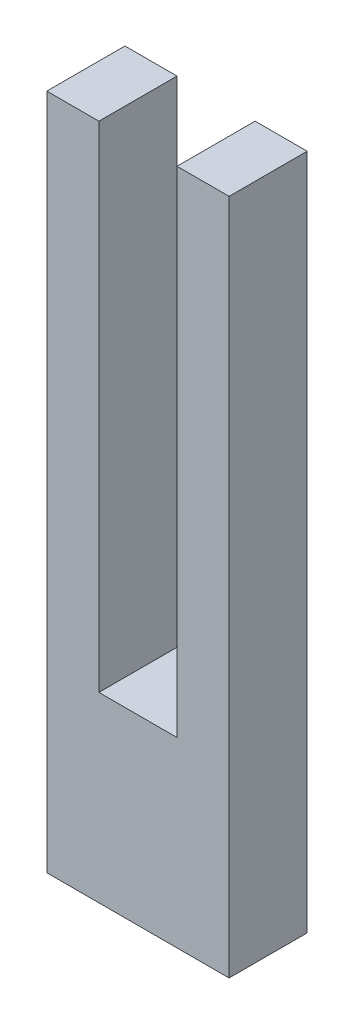
SolidWorks part; units mm, degrees
ref_plane "Alzado" through (0, 0, 0) normal (0, 0, 1) x (1, 0, 0)
ref_plane "Planta" through (0, 0, 0) normal (0, 1, 0) x (1, 0, 0)
ref_plane "Vista lateral" through (0, 0, 0) normal (1, 0, 0) x (0, 0, -1)
sketch "Croquis1" plane through (0, 0, 0) normal (0, 0, 1) x (1, 0, 0)
  line L0 (0, 0) -> (7, 0)
  line L1 (7, 0) -> (7, 26)
  line L2 (7, 26) -> (5, 26)
  line L3 (0, 26) -> (0, 0)
  line L5 (2, 7) -> (5, 7)
  line L8 (2, 7) -> (2, 26)
  line L9 (5, 7) -> (5, 26)
  line L10 (2, 26) -> (0, 26)
  dimension "D1" = 7
  dimension "D2" = 26
  dimension "D4" = 3
extrude "Saliente-Extruir1" add sketch "Croquis1" along normal blind 3
